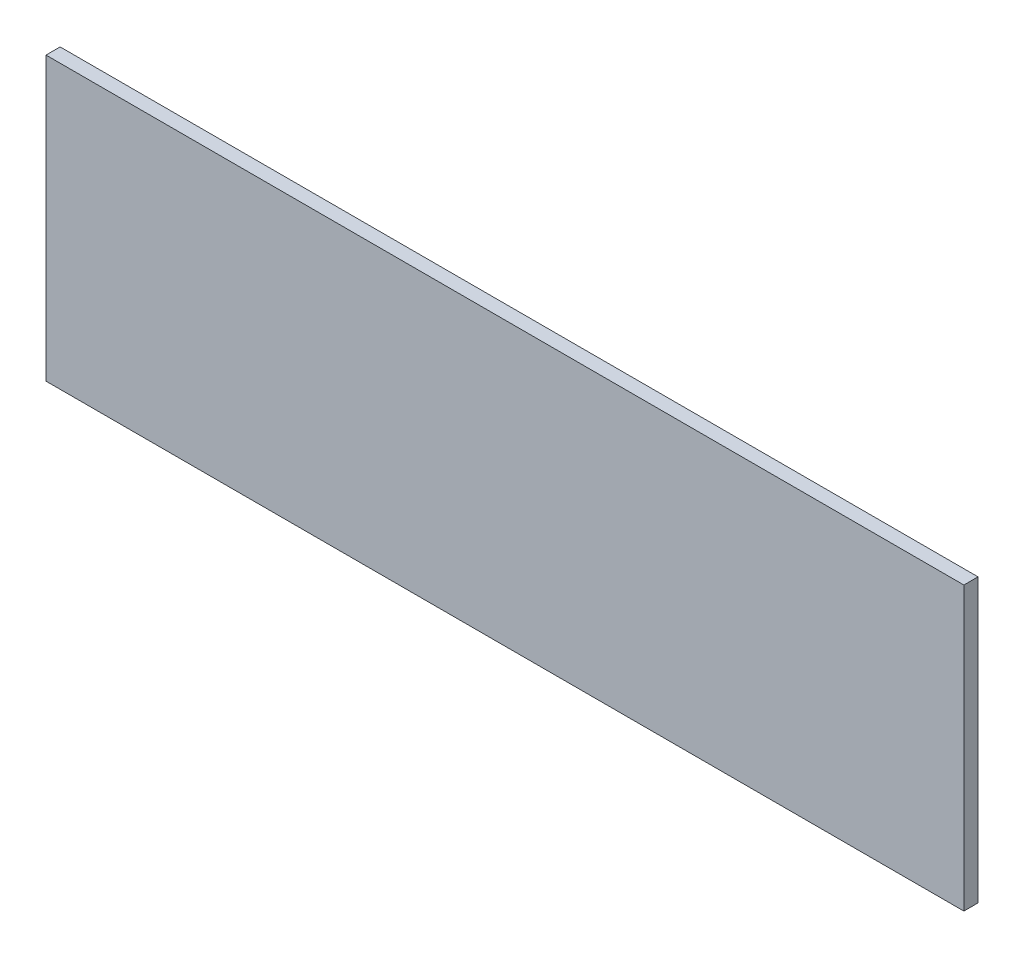
SolidWorks part; units mm, degrees
ref_plane "Plan de face" through (0, 0, 0) normal (0, 0, 1) x (1, 0, 0)
ref_plane "Plan de dessus" through (0, 0, 0) normal (0, 1, 0) x (1, 0, 0)
ref_plane "Plan de droite" through (0, 0, 0) normal (1, 0, 0) x (0, 0, -1)
sketch "Esquisse1" plane through (0, 0, 0) normal (0, 0, 1) x (1, 0, 0)
  line L1 (0, 0) -> (650, 0)
  line L2 (0, 0) -> (0, 200)
  line L3 (0, 200) -> (650, 200)
  line L4 (650, 0) -> (650, 200)
  dimension "D1" = 200
  dimension "D2" = 650
extrude "Boss.-Extru.1" add sketch "Esquisse1" along normal blind 10
